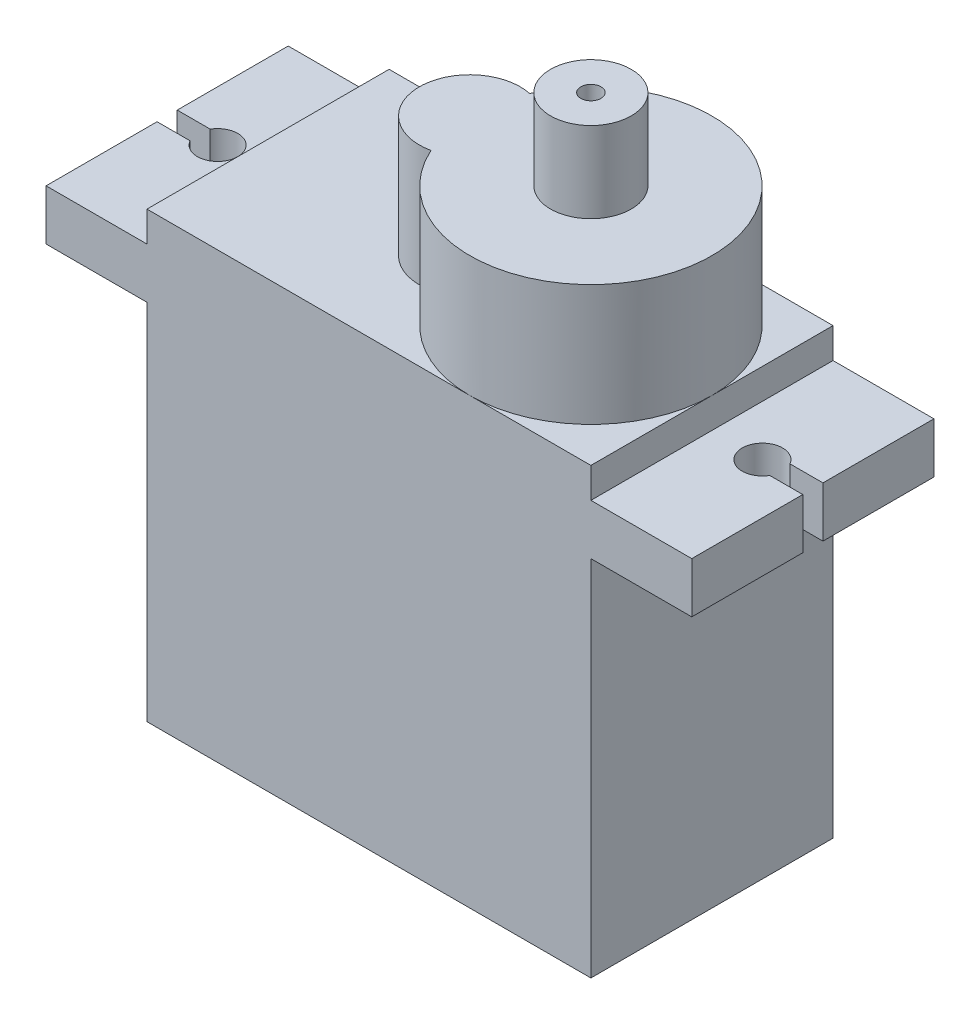
SolidWorks part; units mm, degrees
ref_plane "前视基准面" through (0, 0, 0) normal (0, 0, 1) x (1, 0, 0)
ref_plane "上视基准面" through (0, 0, 0) normal (0, 1, 0) x (1, 0, 0)
ref_plane "右视基准面" through (0, 0, 0) normal (1, 0, 0) x (0, 0, -1)
sketch "草图9" plane through (0, 0, 0) normal (0, 0, 1) x (1, 0, 0)
  line L1 (11, -16.5909) -> (-11, -16.5909)
  line L2 (-11, -16.5909) -> (-11, 1.4091)
  line L3 (-11, 1.4091) -> (-16, 1.4091)
  line L4 (-16, 1.4091) -> (-16, 3.9091)
  line L5 (-16, 3.9091) -> (-11, 3.9091)
  line L6 (-11, 3.9091) -> (-11, 5.4091)
  line L7 (-11, 5.4091) -> (11, 5.4091)
  line L9 (0, -1002) -> (0, -16.5909) construction
  line L10 (11, 3.9091) -> (11, 5.4091)
  line L11 (16, 3.9091) -> (11, 3.9091)
  line L12 (16, 1.4091) -> (16, 3.9091)
  line L13 (11, 1.4091) -> (16, 1.4091)
  line L14 (11, -16.5909) -> (11, 1.4091)
  line L15 (0, 5.4091) -> (0, 48998) construction
  dimension "D1" = 11
  dimension "D2" = 18
  dimension "D3" = 2.5
  dimension "D4" = 5
  dimension "D6" = 22
extrude "凸台-拉伸5" add sketch "草图9" along normal blind 12
ref_plane "基准面12" through (0, 5.4091, 0) normal (0, -1, 0) x (-1, 0, 0)
sketch "草图10" plane through (0, 5.4091, 0) normal (0, -1, 0) x (-1, 0, 0)
  line L0 (-11, -12) -> (-11, 0) construction
  arc A0 (0.4792, -3.5549) -> (0.4792, -8.4451) centre (-5, -6) ccw
  arc A1 (0.4792, -8.4451) -> (0.4792, -3.5549) centre (1, -6) ccw
  dimension "D1" = 12
  dimension "D3" = 2.5
  dimension "D2" = 6
extrude "凸台-拉伸6" add sketch "草图10" against normal blind 6
ref_plane "基准面13" through (0, 11.4091, 0) normal (0, -1, 0) x (-1, 0, 0)
sketch "草图11" plane through (0, 11.4091, 0) normal (0, -1, 0) x (-1, 0, 0)
  circle A0 centre (-5, -6) radius 2
  circle A1 centre (-5, -6) radius 0.5
extrude "凸台-拉伸7" add sketch "草图11" against normal blind 4
ref_plane "基准面14" through (0, 3.9091, 0) normal (0, -1, 0) x (-1, 0, 0)
sketch "草图13" plane through (0, 3.9091, 0) normal (0, -1, 0) x (-1, 0, 0)
  line L0 (11, -12) -> (11, 0) construction
  line L1 (-16, -12) -> (-16, 0) construction
  line L2 (11, 0) -> (16, 0) construction
  line L3 (-16, 0) -> (-11, 0) construction
  line L4 (-16, -12) -> (-16, 0) construction
  line L5 (-14.366, -6.5) -> (-16, -6.5)
  line L7 (-14.366, -5.5) -> (-16, -5.5)
  line L8 (-16, -6.5) -> (-16, -5.5)
  line L11 (16, -12) -> (16, 0) construction
  line L12 (14.366, -5.5) -> (16, -5.5)
  line L14 (14.366, -6.5) -> (16, -6.5)
  line L15 (16, -5.5) -> (16, -6.5)
  arc A0 (14.366, -5.5) -> (14.366, -6.5) centre (13.5, -6) ccw
  arc A1 (-14.366, -6.5) -> (-14.366, -5.5) centre (-13.5, -6) ccw
  point P12 (-14.5, -6)
  point P19 (14.5, -6)
  dimension "D1" = 2.5
  dimension "D6" = 1
  dimension "D7" = 1
  dimension "D2" = 2.5
  dimension "D3" = 6
  dimension "D4" = 6
  dimension "D5" = 1
extrude "切除-拉伸4" cut sketch "草图13" along normal blind 3
sketch "草图15" plane through (0, 15.4091, 0) normal (0, 1, 0) x (1, 0, 0)
  circle A0 centre (5, -6) radius 0.5
  dimension "D1" = 1
extrude "切除-拉伸5" cut sketch "草图15" against normal through all
